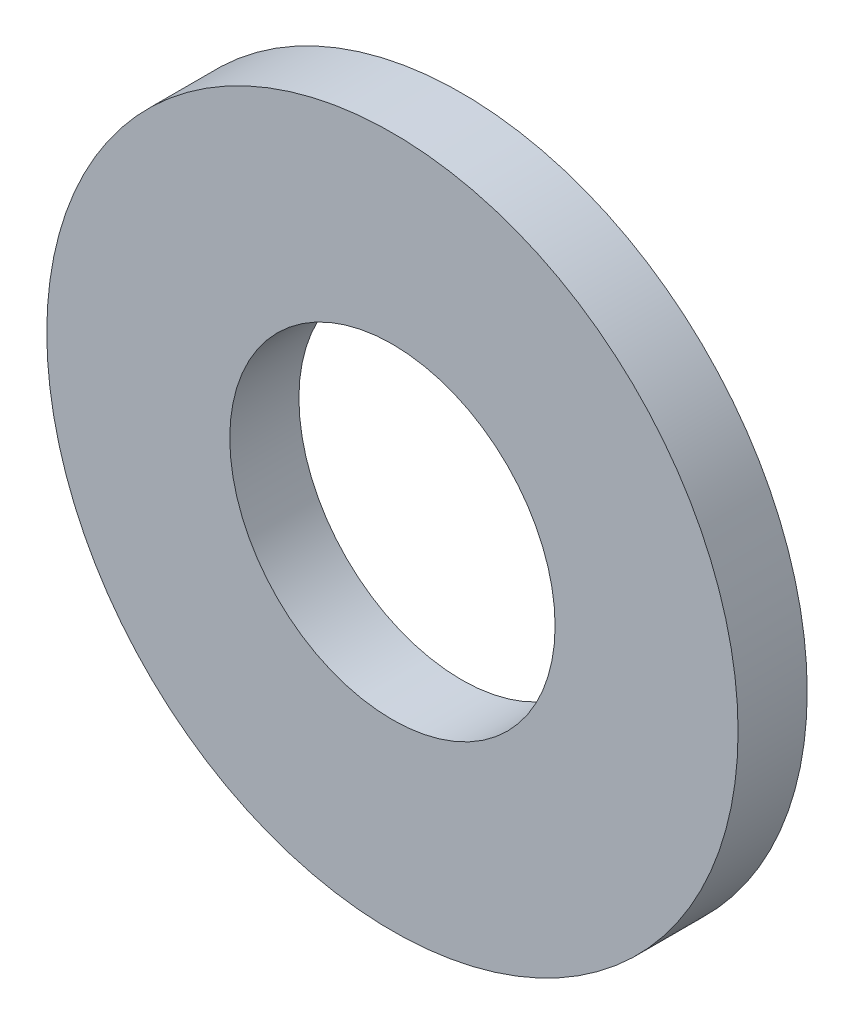
SolidWorks part; units mm, degrees
ref_plane "Спереди" through (0, 0, 0) normal (0, 0, 1) x (1, 0, 0)
ref_plane "Сверху" through (0, 0, 0) normal (0, 1, 0) x (1, 0, 0)
ref_plane "Справа" through (0, 0, 0) normal (1, 0, 0) x (0, 0, -1)
sketch "Эскиз1" plane through (0, 0, 0) normal (0, 0, 1) x (1, 0, 0)
  circle A0 centre (0, 0) radius 4
  circle A1 centre (0, 0) radius 8.5
  dimension "D1" = 17
  dimension "D2" = 8
extrude "Бобышка-Вытянуть1" add sketch "Эскиз1" along normal blind 1.7
